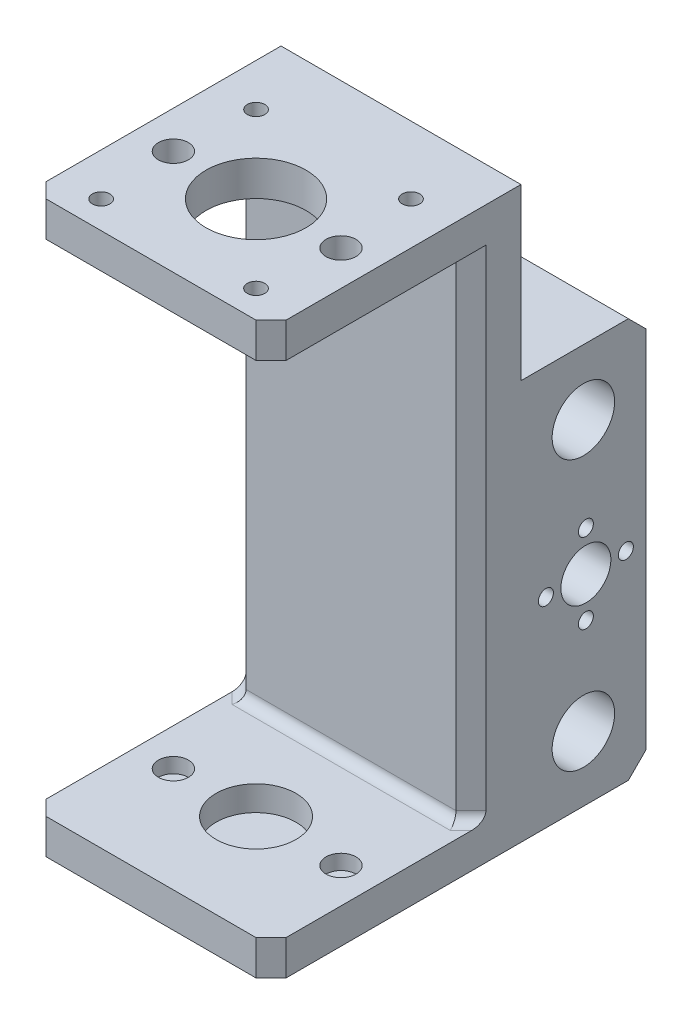
SolidWorks part; units mm, degrees
ref_plane "前基準面" through (0, 0, 0) normal (0, 0, 1) x (1, 0, 0)
ref_plane "上基準面" through (0, 0, 0) normal (0, 1, 0) x (1, 0, 0)
ref_plane "右基準面" through (0, 0, 0) normal (1, 0, 0) x (0, 0, -1)
sketch "草圖1" plane through (0, 0, 0) normal (0, 0, 1) x (1, 0, 0)
  line L0 (-24, -7) -> (24, -7) construction
  line L1 (-24, 50) -> (24, 50)
  line L2 (-24, 50) -> (-24, -50)
  line L3 (-24, -50) -> (24, -50)
  line L4 (24, 50) -> (24, -50)
  line L5 (0, 0) -> (0, 50) construction
  line L6 (-10, 30) -> (-10, 10) construction
  line L7 (24, -7) -> (24, 20) construction
  line L8 (24, 20) -> (-24, 20) construction
  point P4 (0, 50)
  point P6 (-24, 0)
  point P27 (-10, 20)
  dimension "D1" = 17
  dimension "D3" = 48
  dimension "D4" = 20
  dimension "D6" = 10
  dimension "D7" = 10
  dimension "D8" = 100
  dimension "D9" = 43
  dimension "D10" = 27
  dimension "D11" = 27
extrude "填料-伸長1" add sketch "草圖1" along normal blind 10
sketch "草圖4" plane through (0, 50, 0) normal (0, 1, 0) x (1, 0, 0)
  line L1 (21, -50) -> (21, -8) construction
  line L2 (0, -50) -> (0, 0) construction
  line L3 (-24, -10) -> (-24, 0) construction
  line L4 (21, -8) -> (-21, -8) construction
  line L5 (-21, -8) -> (-21, -50) construction
  line L6 (21, -29) -> (-21, -29) construction
  line L7 (21, -12) -> (-21, -12) construction
  line L8 (24, 0) -> (-24, 0)
  line L9 (24, 0) -> (24, -50)
  line L10 (24, -50) -> (-24, -50)
  line L11 (-24, 0) -> (-24, -50)
  circle A0 centre (0, -29) radius 10
  circle A1 centre (17, -29) radius 3
  circle A2 centre (17, -29) radius 6 construction
  circle A3 centre (-16.534, -29) radius 3
  circle A4 centre (15.5, -44.5) radius 1.75
  circle A5 centre (15.5, -13.5) radius 1.75
  circle A6 centre (-15.5, -13.5) radius 1.75
  circle A7 centre (-15.5, -44.5) radius 1.75
  point P9 (0, -29)
  dimension "D1" = 20
  dimension "D6" = 6
  dimension "D5" = 12
  dimension "D4" = 3.5
  dimension "D2" = 21
  dimension "D3" = 42
  dimension "D7" = 5.5
  dimension "D8" = 48
  dimension "D9" = 50
  dimension "D10" = 5.5
  dimension "D11" = 42
  dimension "D12" = 17
  dimension "D13" = 38
  dimension "D14" = 17
extrude "填料-伸長3" add sketch "草圖4" along normal blind 7
sketch "草圖6" plane through (0, -50, 0) normal (0, -1, 0) x (1, 0, 0)
  line L1 (-24, 0) -> (24, 0)
  line L2 (-24, 0) -> (-24, 50)
  line L3 (-24, 50) -> (24, 50)
  line L4 (24, 0) -> (24, 50)
  circle A0 centre (0, 29) radius 8
  circle A1 centre (-16.534, 29) radius 3
  circle A2 centre (17, 29) radius 3
  dimension "D1" = 16
  dimension "D2" = 6
extrude "填料-伸長4" add sketch "草圖6" along normal blind 7
sketch "草圖3" plane through (0, 0, 0) normal (0, 0, -1) x (-1, 0, 0)
  line L0 (24, -57) -> (-24, -57) construction
  line L1 (-24, 23) -> (24, 23)
  line L2 (-24, 23) -> (-24, -57)
  line L3 (-24, -57) -> (24, -57)
  line L4 (24, 23) -> (24, -57)
  line L6 (-24, -17) -> (24, -17) construction
  line L7 (-24, -57) -> (-24, 57) construction
  line L8 (24, 57) -> (24, -57) construction
  point P16 (24, -17)
  dimension "D1" = 80
extrude "填料-伸長2" add sketch "草圖3" along normal blind 25
chamfer "導角1" distance 3 angle 45 6 edges at (24, 0, 10) (-24, 0, 10) (24, -53.5, 50) (-24, -53.5, 50) (24, 53.5, 50) (-24, 53.5, 50)
fillet "圓角1" radius 2 3 edges at (-22.5, -50, 8.5) (22.5, -50, 8.5) (0, -50, 10)
sketch "草圖7" plane through (0, -57, 0) normal (0, -1, 0) x (1, 0, 0)
  circle A0 centre (17, 29) radius 3
  circle A1 centre (-16.534, 29) radius 3
extrude "填料-伸長5" add sketch "草圖7" against normal blind 4 separate body
sketch "草圖8" plane through (24, 0, 0) normal (1, 0, 0) x (0, 0, -1)
  line L0 (25, 23) -> (25, -57) construction
  line L1 (25, -17) -> (0, -17) construction
  line L2 (0, 4) -> (0, -47) construction
  line L3 (0, 23) -> (0, 57) construction
  line L4 (25, 23) -> (0, 23) construction
  circle A0 centre (13, -17) radius 5
  circle A1 centre (21, -17) radius 1.5
  circle A2 centre (13, -25) radius 1.5
  circle A3 centre (5, -17) radius 1.5
  circle A4 centre (13, -9) radius 1.5
  circle A5 centre (12.5, 10) radius 6.25
  circle A6 centre (12.5, -43.9954) radius 6.25
  point P4 (25, -17)
  point P16 (13, -17)
  point P31 (12.5, 23)
  dimension "D2" = 10
  dimension "D3" = 3
  dimension "D7" = 12.5
  dimension "D8" = 12.5
  dimension "D1" = 12
  dimension "D4" = 8
  dimension "D6" = 13
  dimension "D9" = 27
  dimension "D10" = 27
  dimension "D5" = 4
extrude "除料-伸長3" cut sketch "草圖8" against normal through all
sketch "草圖9" plane through (0, 50, 0) normal (0, -1, 0) x (1, 0, 0)
  circle A0 centre (-15.5, 44.5) radius 3
  circle A1 centre (-15.5, 13.5) radius 3
  circle A2 centre (15.5, 13.5) radius 3
  circle A3 centre (15.5, 44.5) radius 3
  dimension "D1" = 6
  dimension "D2" = 6
  dimension "D3" = 6
  dimension "D4" = 6
extrude "除料-伸長4" cut sketch "草圖9" against normal blind 3
chamfer "導角5" distance 3.5 angle 45 2 edges at (0, 23, -25) (0, -57, -25)
sketch "草圖10" plane through (0, -57, 0) normal (0, -1, 0) x (1, 0, 0)
  circle A0 centre (0, 29) radius 8
extrude "填料-伸長6" add sketch "草圖10" against normal blind 2 separate body
